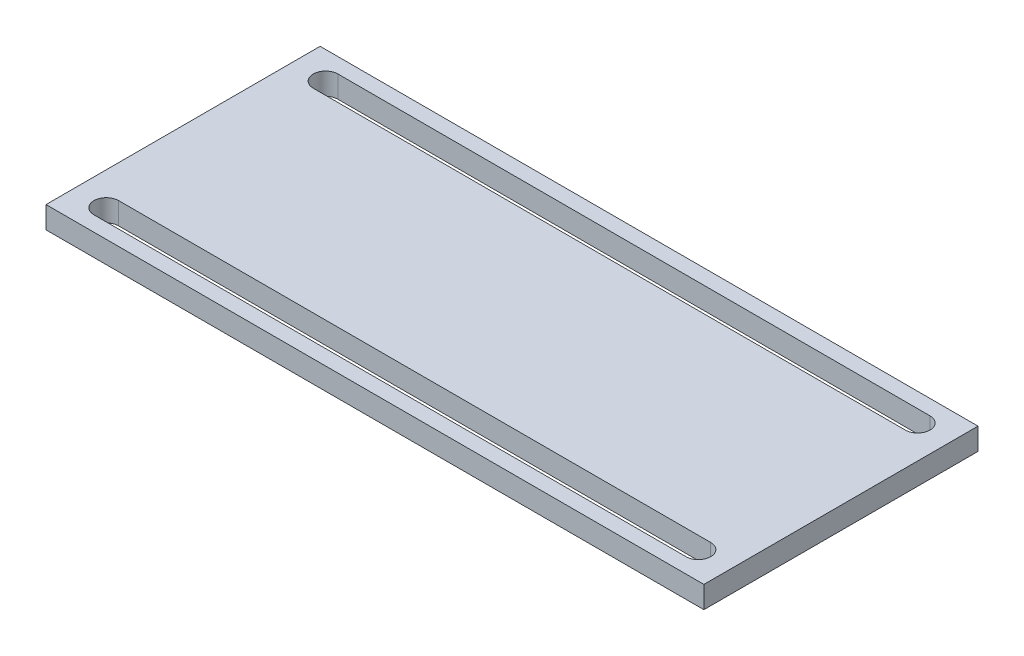
SolidWorks part; units mm, degrees
ref_plane "Front Plane" through (0, 0, 0) normal (0, 0, 1) x (1, 0, 0)
ref_plane "Top Plane" through (0, 0, 0) normal (0, 1, 0) x (1, 0, 0)
ref_plane "Right Plane" through (0, 0, 0) normal (1, 0, 0) x (0, 0, -1)
sketch "Sketch1" plane through (0, 0, 0) normal (0, 1, 0) x (1, 0, 0)
  line L1 (-60, -25) -> (60, -25)
  line L2 (-60, -25) -> (-60, 25)
  line L3 (-60, 25) -> (60, 25)
  line L4 (60, -25) -> (60, 25)
  line L5 (-60, -25) -> (60, 25) construction
  line L6 (-60, 25) -> (60, -25) construction
  point P0 (0, 0)
  dimension "D1" = 120
  dimension "D2" = 50
extrude "Boss-Extrude1" add sketch "Sketch1" along normal blind 4
sketch "Sketch2" plane through (0, 4, 0) normal (0, 1, 0) x (1, 0, 0)
  line L0 (-54, 20) -> (54, 20) construction
  line L1 (-54, 22.25) -> (54, 22.25)
  line L2 (-54, 17.75) -> (54, 17.75)
  line L3 (-54, -20) -> (54, -20) construction
  line L4 (-54, -17.75) -> (54, -17.75)
  line L5 (-54, -22.25) -> (54, -22.25)
  line L7 (-60, 25) -> (-60, -25) construction
  line L8 (60, -25) -> (60, 25) construction
  line L9 (-54, 20) -> (-54, -20) construction
  arc A0 (-54, 22.25) -> (-54, 17.75) centre (-54, 20) ccw
  arc A1 (54, 17.75) -> (54, 22.25) centre (54, 20) ccw
  arc A2 (-54, -17.75) -> (-54, -22.25) centre (-54, -20) ccw
  arc A3 (54, -22.25) -> (54, -17.75) centre (54, -20) ccw
  point P2 (0, 20)
  point P7 (0, -20)
  point P14 (-60, 0)
  point P15 (-54, 0)
  point P16 (-54, 12.0457)
  point P23 (-54, -15.7949)
  point P24 (-54, 22.4779)
  dimension "D4" = 2.25
  dimension "D5" = 2.25
  dimension "D1" = 40
  dimension "D2" = 6
  dimension "D3" = 6
extrude "Cut-Extrude1" cut sketch "Sketch2" against normal through all
